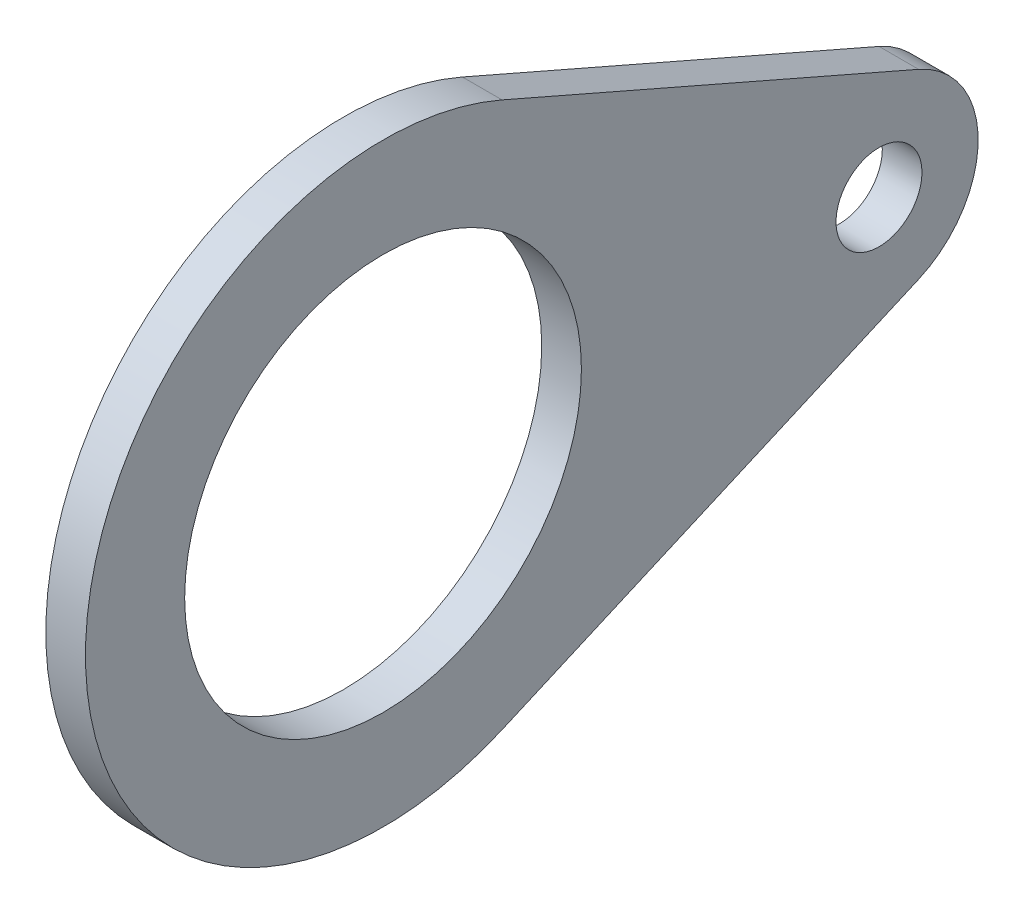
SolidWorks part; units mm, degrees
material "Q235"
ref_plane "前视基准面" through (0, 0, 0) normal (0, 0, 1) x (1, 0, 0)
ref_plane "上视基准面" through (0, 0, 0) normal (0, 1, 0) x (1, 0, 0)
ref_plane "右视基准面" through (0, 0, 0) normal (1, 0, 0) x (0, 0, -1)
sketch "草图1" plane through (0, 0, 0) normal (1, 0, 0) x (0, 0, -1)
  line L0 (0, 0) -> (95.7823, 0) construction
  line L1 (18, 41.2432) -> (81, 13.7477)
  line L2 (18, -41.2432) -> (81, -13.7477)
  circle A0 centre (0, 0) radius 30
  circle A1 centre (75, 0) radius 6.5
  arc A2 (18, 41.2432) -> (18, -41.2432) centre (0, 0) ccw
  arc A3 (81, -13.7477) -> (81, 13.7477) centre (75, 0) ccw
  dimension "D1" = 60
  dimension "D2" = 13
  dimension "D4" = 45
  dimension "D5" = 15
  dimension "D3" = 75
extrude "凸台-拉伸1" add sketch "草图1" along normal blind 6
